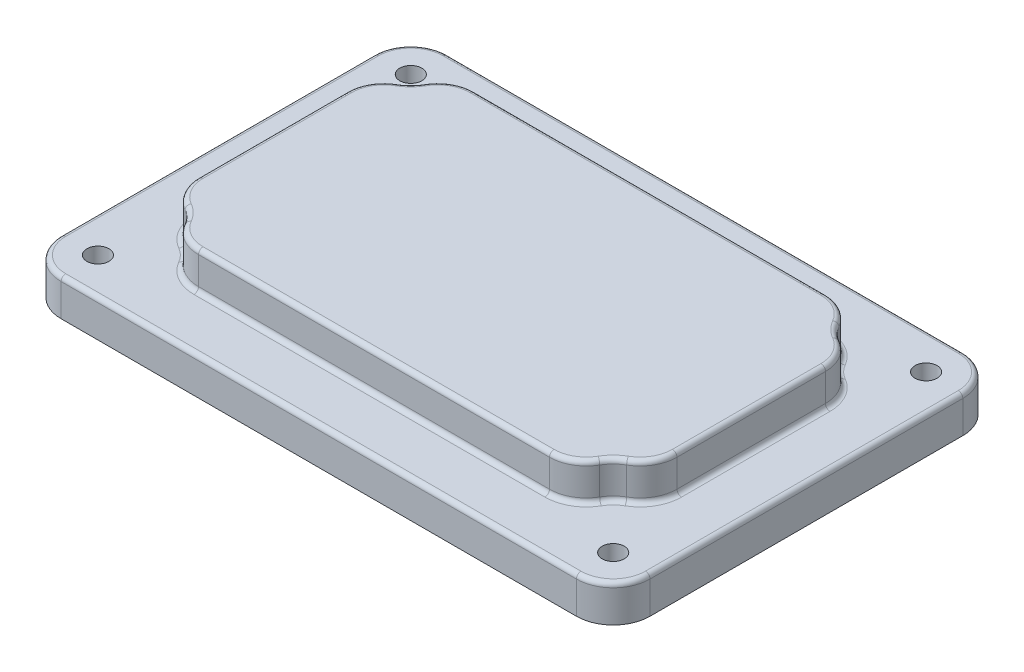
SolidWorks part; units mm, degrees
material "Cast Alloy Steel"
ref_plane "Front Plane" through (0, 0, 0) normal (0, 0, 1) x (1, 0, 0)
ref_plane "Top Plane" through (0, 0, 0) normal (0, 1, 0) x (1, 0, 0)
ref_plane "Right Plane" through (0, 0, 0) normal (1, 0, 0) x (0, 0, -1)
sketch "Sketch1" plane through (0, 0, 0) normal (0, 1, 0) x (1, 0, 0)
  line L1 (-44.45, 33.3375) -> (44.45, 33.3375)
  line L2 (-50.8, 26.9875) -> (-50.8, -26.9875)
  line L3 (-44.45, -33.3375) -> (44.45, -33.3375)
  line L4 (50.8, 26.9875) -> (50.8, -26.9875)
  line L5 (-50.8, 33.3375) -> (50.8, -33.3375) construction
  line L6 (-50.8, -33.3375) -> (50.8, 33.3375) construction
  arc A0 (44.45, -33.3375) -> (50.8, -26.9875) centre (44.45, -26.9875) ccw
  arc A1 (-50.8, -26.9875) -> (-44.45, -33.3375) centre (-44.45, -26.9875) ccw
  arc A2 (44.45, 33.3375) -> (50.8, 26.9875) centre (44.45, 26.9875) cw
  arc A3 (-44.45, 33.3375) -> (-50.8, 26.9875) centre (-44.45, 26.9875) ccw
  point P0 (0, 0)
  dimension "D3" = 12.7
  dimension "D1" = 66.675
  dimension "D2" = 101.6
extrude "Base" add sketch "Sketch1" along normal blind 6.35
sketch "Sketch2" plane through (0, 6.35, 0) normal (0, 1, 0) x (1, 0, 0)
  line L8 (41.275, -23.8125) -> (41.275, 23.8125)
  line L9 (41.275, 23.8125) -> (-41.275, 23.8125)
  line L10 (-41.275, 23.8125) -> (-41.275, -23.8125)
  line L11 (-41.275, -23.8125) -> (41.275, -23.8125)
  line L12 (41.275, -23.8125) -> (41.275, 23.8125)
  line L13 (41.275, 23.8125) -> (-41.275, 23.8125)
  line L14 (-41.275, 23.8125) -> (-41.275, -23.8125)
  line L15 (-41.275, -23.8125) -> (41.275, -23.8125)
  dimension "D1" = 9.525
extrude "Top Boss" add sketch "Sketch2" along normal blind 6.35
sketch "Sketch3" plane through (0, 12.7, 0) normal (0, 1, 0) x (1, 0, 0)
  line L0 (0, 0) -> (37.3306, 0) construction
  line L1 (0, 0) -> (0, 30.1625) construction
  circle A0 centre (41.275, 23.8125) radius 6.35
  circle A1 centre (-41.275, 23.8125) radius 6.35
  circle A2 centre (-41.275, -23.8125) radius 6.35
  circle A3 centre (41.275, -23.8125) radius 6.35
  dimension "D1" = 12.7
extrude "Corner Cuts" cut sketch "Sketch3" against normal up to surface (6.35 mm away) up to face at (0, 6.35, 0)
fillet "Fillet1" radius 6.35 8 edges at (-34.925, 9.525, 23.8125) (41.275, 9.525, -17.4625) (34.925, 9.525, -23.8125) (-34.925, 9.525, -23.8125) (-41.275, 9.525, -17.4625) (-41.275, 9.525, 17.4625) (34.925, 9.525, 23.8125) (41.275, 9.525, 17.4625)
shell "Shell1" thickness 3.175
sketch "Sketch4" plane through (0, 0, 0) normal (0, -1, 0) x (1, 0, 0)
  circle A0 centre (44.45, 26.9875) radius 6.35
  circle A1 centre (-44.45, 26.9875) radius 6.35
  circle A2 centre (-44.45, -26.9875) radius 6.35
  circle A3 centre (44.45, -26.9875) radius 6.35
  arc A4 (-50.8, -26.9875) -> (-44.45, -33.3375) centre (-44.45, -26.9875) ccw construction
extrude "Boss-Extrude3" add sketch "Sketch4" against normal up to surface (3.175 mm away) up to face at (0, 3.175, 0)
fillet "Fillet2" radius 0.7874 40 edges at (0, 6.35, 33.3375) (-48.9401, 6.35, 31.4776) (-50.8, 6.35, 0) (-48.9401, 6.35, -31.4776) (0, 6.35, -33.3375) (48.9401, 6.35, -31.4776) (50.8, 6.35, 0) (48.9401, 6.35, 31.4776) (40.4243, 6.35, -15.989) (36.7849, 12.7, -19.3224) (36.7849, 6.35, -19.3224) (33.4515, 6.35, -22.9618) (0, 6.35, -23.8125) (-33.4515, 6.35, -22.9618) (-36.7849, 12.7, -19.3224) (-36.7849, 6.35, -19.3224) (-40.4243, 6.35, -15.989) (-41.275, 6.35, 0) (-40.4243, 6.35, 15.989) (-36.7849, 12.7, 19.3224) (-36.7849, 6.35, 19.3224) (-33.4515, 6.35, 22.9618) (0, 6.35, 23.8125) (33.4515, 6.35, 22.9618) (36.7849, 12.7, 19.3224) (36.7849, 6.35, 19.3224) (40.4243, 6.35, 15.989) (41.275, 6.35, 0) (40.4243, 12.7, 15.989) (33.4515, 12.7, 22.9618) (0, 12.7, 23.8125) (-33.4515, 12.7, 22.9618) (-40.4243, 12.7, 15.989) (-41.275, 12.7, 0) (-40.4243, 12.7, -15.989) (-33.4515, 12.7, -22.9618) (0, 12.7, -23.8125) (33.4515, 12.7, -22.9618) (40.4243, 12.7, -15.989) (41.275, 12.7, 0)
fillet "Fillet3" radius 0.7874 56 edges at (39.9599, 0, -22.4974) (39.9599, 3.175, -22.4974) (-39.9599, 0, -22.4974) (-39.9599, 3.175, -22.4974) (-39.9599, 0, 22.4974) (-39.9599, 3.175, 22.4974) (39.9599, 3.175, 22.4974) (39.9599, 0, 22.4974) (47.625, 3.175, 0) (47.625, 1.5875, 21.4882) (47.625, 0, 0) (47.625, 1.5875, -21.4882) (0, 0, -30.1625) (-38.9507, 1.5875, -30.1625) (0, 3.175, -30.1625) (38.9507, 1.5875, -30.1625) (-47.625, 0, 0) (-47.625, 1.5875, 21.4882) (-47.625, 3.175, 0) (-47.625, 1.5875, -21.4882) (0, 0, 30.1625) (38.9507, 1.5875, 30.1625) (0, 3.175, 30.1625) (-38.9507, 1.5875, 30.1625) (0, 3.175, 20.6375) (38.1, 3.175, 0) (0, 3.175, -20.6375) (-38.1, 3.175, 0) (0, 9.525, -20.6375) (-38.1, 9.525, 0) (0, 9.525, 20.6375) (38.1, 9.525, 0) (34.5398, 3.175, -17.0773) (34.5398, 9.525, -17.0773) (-34.5398, 3.175, -17.0773) (-34.5398, 9.525, -17.0773) (-34.5398, 3.175, 17.0773) (-34.5398, 9.525, 17.0773) (34.5398, 3.175, 17.0773) (34.5398, 9.525, 17.0773) (37.6746, 9.525, -14.4015) (37.6746, 3.175, -14.4015) (31.864, 3.175, -20.2121) (31.864, 9.525, -20.2121) (-31.864, 9.525, -20.2121) (-31.864, 3.175, -20.2121) (-37.6746, 3.175, -14.4015) (-37.6746, 9.525, -14.4015) (-37.6746, 9.525, 14.4015) (-37.6746, 3.175, 14.4015) (31.864, 9.525, 20.2121) (31.864, 3.175, 20.2121) (37.6746, 3.175, 14.4015) (37.6746, 9.525, 14.4015) (-31.864, 3.175, 20.2121) (-31.864, 9.525, 20.2121)
hole_wizard "#6 Clearance Hole1" positions "Sketch6" profile "Sketch5" hole size "#6" standard "ANSI Inch" end condition through all
sketch "Sketch6" plane through (0, 6.35, 0) normal (0, 1, 0) x (1, 0, 0)
  point P0 (-44.45, 26.9875)
  point P3 (44.45, 26.9875)
  point P6 (44.45, -26.9875)
  point P9 (-44.45, -26.9875)
sketch "Sketch5" plane through (-44.45, 6.35, -26.9875) normal (1, 0, 0) x (0, 0, 1)
  line L0 (0, 0) -> (0, 6.35)
  line L1 (0, 6.35) -> (1.8986, 6.35)
  line L2 (1.8986, 6.35) -> (1.8986, 0)
  line L5 (1.8986, 0) -> (0, 0)
  line L11 (0, -6.35) -> (0, 107.95) construction
  dimension "Thru Hole Dia." = 3.7973
  dimension "Thru Hole Depth" = 6.35
